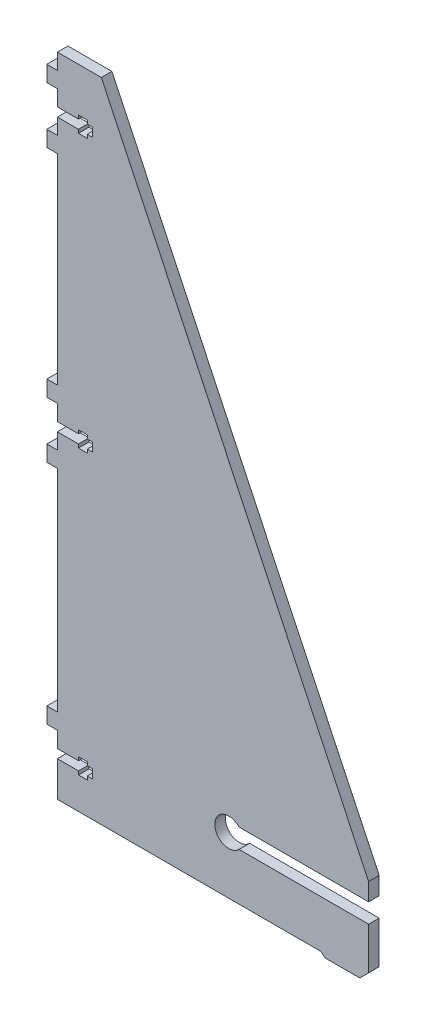
SolidWorks part; units mm, degrees
material "Sosna"
ref_plane "Płaszczyzna przednia" through (0, 0, 0) normal (0, 0, 1) x (1, 0, 0)
ref_plane "Płaszczyzna górna" through (0, 0, 0) normal (0, 1, 0) x (1, 0, 0)
ref_plane "Płaszczyzna prawa" through (0, 0, 0) normal (1, 0, 0) x (0, 0, -1)
sketch "Szkic1" plane through (0, 0, 0) normal (0, 0, 1) x (1, 0, 0)
  line L0 (0, -185) -> (0, 185)
  line L1 (0, 185) -> (25, 185)
  line L3 (177, -185) -> (0, -185)
  line L4 (177, -185) -> (177, -135)
  line L5 (177, -135) -> (25, 185)
  point P4 (0, 0)
  dimension "D1" = 177
  dimension "D2" = 25
  dimension "D3" = 370
  dimension "D4" = 50
extrude "Dodanie-wyciągnięcie1" add sketch "Szkic1" along normal blind 6
chamfer "Sfazowanie1" distance 5 angle 45 1 edges at (177, -185, 3)
sketch "Szkic2" plane through (0, 0, 6) normal (0, 0, 1) x (1, 0, 0)
  line L0 (0, -183) -> (150, -183)
  line L1 (0, 185) -> (0, -185) construction
  line L2 (150, -183) -> (152, -185)
  line L3 (0, -185) -> (172, -185) construction
  line L4 (152, -185) -> (0, -185)
  line L5 (0, -185) -> (0, -183)
  dimension "D1" = 45
  dimension "D2" = 20
  dimension "D3" = 2
extrude "Wytnij-wyciągnięcie1" cut sketch "Szkic2" against normal up to next
sketch "Szkic3" plane through (0, 0, 6) normal (0, 0, 1) x (1, 0, 0)
  line L0 (97.5, -150.5) -> (177, -150.5) construction
  line L1 (177, -180) -> (177, -135) construction
  line L2 (103.3095, -145) -> (177, -145)
  line L3 (177, -145) -> (177, -156)
  line L4 (177, -156) -> (103.3095, -156)
  line L5 (152, -185) -> (172, -185) construction
  line L6 (177, -156) -> (177, -145)
  circle A0 centre (97.5, -150.5) radius 8
  point P7 (89.5, -150.5)
  dimension "D1" = 11
  dimension "D2" = 16
  dimension "D3" = 87.5
  dimension "D4" = 29
extrude "Wytnij-wyciągnięcie2" cut sketch "Szkic3" against normal up to next
sketch "Szkic5" plane through (0, 0, 0) normal (-1, 0, 0) x (0, 0, 1)
  line L4 (6, 167) -> (6, 176)
  line L5 (0, 167) -> (6, 167)
  line L6 (0, 176) -> (0, 167)
  line L7 (6, 176) -> (0, 176)
  line L8 (6, 167) -> (6, 176)
  line L9 (0, 167) -> (6, 167)
  line L10 (0, 176) -> (0, 167)
  line L11 (6, 176) -> (0, 176)
  line L13 (6, 135) -> (6, 144)
  line L14 (0, 135) -> (6, 135)
  line L15 (0, 144) -> (0, 135)
  line L16 (6, 144) -> (0, 144)
  line L17 (6, 135) -> (6, 144)
  line L18 (0, 135) -> (6, 135)
  line L19 (0, 144) -> (0, 135)
  line L20 (6, 144) -> (0, 144)
  line L21 (6, -149) -> (6, -140)
  line L22 (0, -149) -> (6, -149)
  line L23 (0, -140) -> (0, -149)
  line L24 (6, -140) -> (0, -140)
  line L25 (6, -149) -> (6, -140)
  line L26 (0, -149) -> (6, -149)
  line L27 (0, -140) -> (0, -149)
  line L28 (6, -140) -> (0, -140)
  line L29 (6, -11) -> (0, -11)
  line L30 (6, -20) -> (6, -11)
  line L31 (0, -20) -> (6, -20)
  line L32 (0, -11) -> (0, -20)
  line L33 (6, -11) -> (0, -11)
  line L34 (6, -20) -> (6, -11)
  line L35 (0, -20) -> (6, -20)
  line L36 (0, -11) -> (0, -20)
  line L37 (6, 21) -> (0, 21)
  line L38 (6, 12) -> (6, 21)
  line L39 (0, 12) -> (6, 12)
  line L40 (0, 21) -> (0, 12)
  line L41 (6, 21) -> (0, 21)
  line L42 (6, 12) -> (6, 21)
  line L43 (0, 12) -> (6, 12)
  line L44 (0, 21) -> (0, 12)
  dimension "D1" = 0
  dimension "D2" = 0
  dimension "D3" = 0
  dimension "D4" = 0
  dimension "D5" = 0
extrude "Dodanie-wyciągnięcie3" add sketch "Szkic5" along normal blind 6
sketch "Szkic6" plane through (0, 0, 6) normal (0, 0, 1) x (1, 0, 0)
  line L0 (0, 155.5) -> (20, 155.5) construction
  line L1 (0, 167) -> (0, 144) construction
  line L2 (0, 158) -> (12, 158)
  line L3 (12, 158) -> (12, 160)
  line L4 (12, 160) -> (17, 160)
  line L5 (17, 160) -> (17, 158)
  line L6 (17, 158) -> (20, 158)
  line L7 (20, 158) -> (20, 153)
  line L8 (0, 158) -> (0, 153)
  line L9 (17, 153) -> (20, 153)
  line L10 (17, 151) -> (17, 153)
  line L11 (12, 151) -> (17, 151)
  line L12 (12, 153) -> (12, 151)
  line L13 (0, 153) -> (12, 153)
  line L14 (0, 3) -> (12, 3)
  line L15 (12, 3) -> (12, 5)
  line L16 (12, 5) -> (17, 5)
  line L17 (17, 5) -> (17, 3)
  line L18 (17, 3) -> (20, 3)
  line L19 (20, 3) -> (20, -2)
  line L20 (0, 3) -> (0, -2)
  line L26 (0, 0.5) -> (20, 0.5) construction
  line L27 (12, -158) -> (0, -158)
  line L28 (17, -2) -> (20, -2)
  line L29 (17, -4) -> (17, -2)
  line L30 (12, -4) -> (17, -4)
  line L31 (12, -2) -> (12, -4)
  line L32 (0, -2) -> (12, -2)
  line L34 (20, -158) -> (20, -163)
  line L35 (0, -158) -> (0, -160.5)
  line L36 (0, 12) -> (0, -11) construction
  line L37 (12, -163) -> (0, -163)
  line L38 (0, -160.5) -> (20, -160.5) construction
  line L39 (0, -149) -> (0, -183) construction
  line L40 (12, -165) -> (12, -163)
  line L41 (20, -158) -> (17, -158)
  line L42 (17, -158) -> (17, -156)
  line L43 (17, -156) -> (12, -156)
  line L44 (12, -156) -> (12, -158)
  line L45 (17, -165) -> (12, -165)
  line L46 (-6, -149) -> (0, -149) construction
  line L47 (17, -163) -> (17, -165)
  line L48 (20, -163) -> (17, -163)
  line L49 (0, -158) -> (0, -163)
  line M24 (0, 167) -> (0, 144)
  line M32 (0, 12) -> (0, -11)
  line M40 (0, -149) -> (0, -183)
  dimension "D1" = 12
  dimension "D2" = 5
  dimension "D3" = 3
  dimension "D4" = 2.5
  dimension "D5" = 4.5
  dimension "D6" = 2.5
  dimension "D7" = 4.5
  dimension "D8" = 11.5
  dimension "D10" = 4.5
  dimension "D9" = 2.5
extrude "Wytnij-wyciągnięcie3" cut sketch "Szkic6" against normal up to next contours L48 L34 L41 L42 L43 L44 L27 L37 L40 L45 L47 M40 | L32 L31 L30 L29 L28 L19 L18 L17 L16 L15 L14 M32 | L13 L12 L11 L10 L9 L7 L6 L5 L4 L3 L2 M24
equation "\"D6@Szkic6\"=\"D4@Szkic6\""
equation "\"D7@Szkic6\"=\"D5@Szkic6\""
equation "\"D10@Szkic6\"=\"D7@Szkic6\""
equation "\"D9@Szkic6\"=\"D6@Szkic6\""
